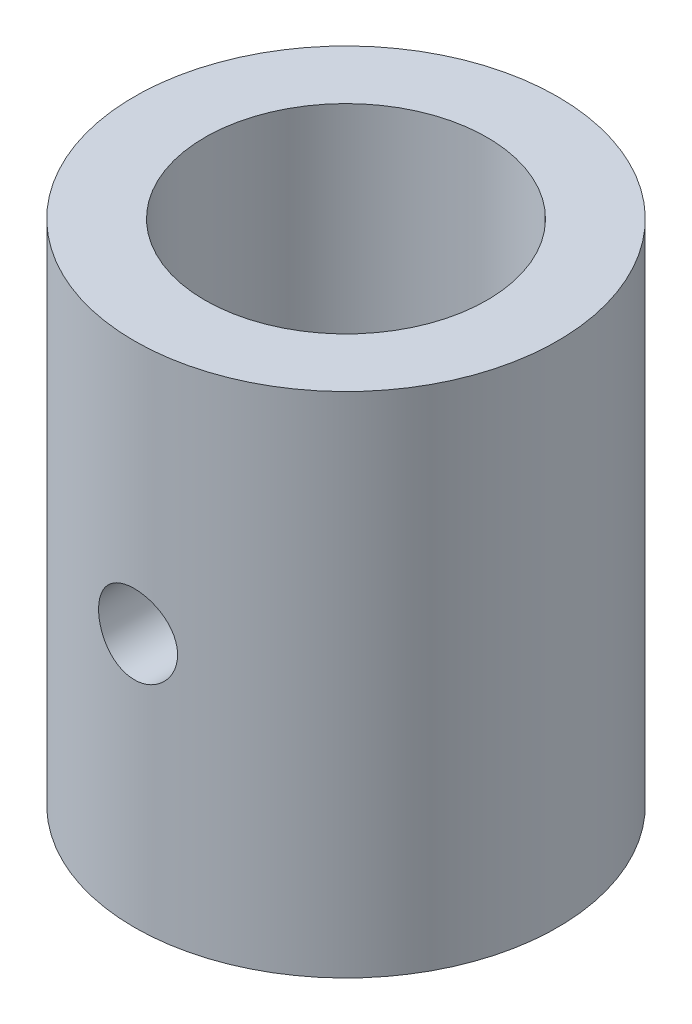
SolidWorks part; units mm, degrees
material "6061-T6 (SS)"
ref_plane "Front Plane" through (0, 0, 0) normal (0, 0, 1) x (1, 0, 0)
ref_plane "Top Plane" through (0, 0, 0) normal (0, 1, 0) x (1, 0, 0)
ref_plane "Right Plane" through (0, 0, 0) normal (1, 0, 0) x (0, 0, -1)
sketch "Sketch1" plane through (0, 0, 0) normal (0, 1, 0) x (1, 0, 0)
  circle A0 centre (0, 0) radius 4.7625
  circle A1 centre (0, 0) radius 3.175
  dimension "D1" = 9.525
  dimension "D2" = 6.35
extrude "Boss-Extrude1" add sketch "Sketch1" along normal blind 11.43
ref_plane "Plane1" through (0, 0, 4.7625) normal (0, 0, 1) x (1, 0, 0)
sketch "Sketch2" plane through (0, 0, 4.7625) normal (0, 0, 1) x (1, 0, 0)
  line L0 (0, 11.43) -> (0, 0) construction
  line L1 (4.7625, 11.43) -> (-4.7625, 11.43) construction
  point P5 (0, 5.715)
hole_wizard "#2-56 Tapped Hole1" positions "Sketch2" profile "Sketch3" tap size "#2-56" standard "ANSI Inch"
sketch "Sketch3" plane through (0, 5.715, 4.7625) normal (1, 0, 0) x (0, -1, 0)
  line L0 (0, 0) -> (0, 6.1222)
  line L1 (0, 6.1222) -> (0.889, 5.588)
  line L2 (0.889, 5.588) -> (0.889, 0)
  line L5 (0.889, 0) -> (0, 0)
  line L10 (0, 6.1222) -> (-0.889, 5.588) construction
  line L11 (0, -6.35) -> (0, 107.95) construction
  dimension "Tap Drill Dia." = 1.778
  dimension "Tap Drill Depth" = 5.588
  dimension "Drill Angle" = 118
cosmetic thread "Hole Thread1" parameters "D1"=4.318, "D2"=2.1844
